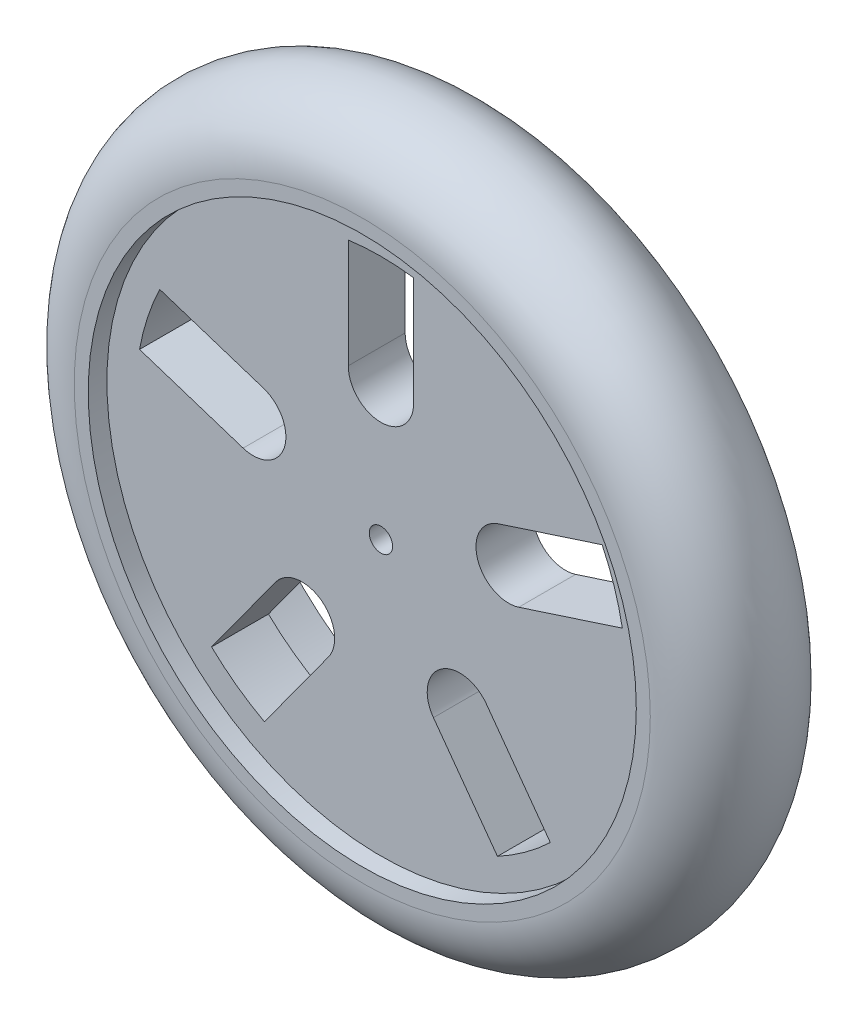
SolidWorks part; units mm, degrees
ref_plane "Front Plane" through (0, 0, 0) normal (0, 0, 1) x (1, 0, 0)
ref_plane "Top Plane" through (0, 0, 0) normal (0, 1, 0) x (1, 0, 0)
ref_plane "Right Plane" through (0, 0, 0) normal (1, 0, 0) x (0, 0, -1)
sketch "Sketch1" plane through (0, 0, 0) normal (1, 0, 0) x (0, 0, -1)
  line L0 (45.339, 0) -> (-45.339, 0)
  line L2 (-45.339, 195.961) -> (-45.339, 0)
  line L3 (-45.339, 0) -> (45.339, 0) construction
  line L4 (45.339, 195.961) -> (45.339, 0)
  arc A0 (45.339, 195.961) -> (-45.339, 195.961) centre (0, 195.961) ccw
  dimension "D1" = 90.678
  dimension "D2" = 195.961
revolve "Revolve1" add sketch "Sketch1" angle 360 about L3
sketch "Sketch2" plane through (0, 0, 45.339) normal (0, 0, 1) x (1, 0, 0)
  circle A0 centre (0, 0) radius 7.9375
  dimension "D1" = 15.875
extrude "Extrude1" cut sketch "Sketch2" against normal through all
sketch "Sketch3" plane through (0, 0, -45.339) normal (0, 0, -1) x (-1, 0, 0)
  circle A0 centre (0, 0) radius 186.436
  circle A1 centre (0, 0) radius 12.7
  dimension "D1" = 25.4
  dimension "D2" = 372.872
extrude "Extrude2" cut sketch "Sketch3" against normal blind 12.2936
sketch "Sketch4" plane through (0, 0, -33.0454) normal (0, 0, -1) x (-1, 0, 0)
  circle A0 centre (0, 0) radius 12.7
  circle A2 centre (0, 0) radius 186.436
  circle A3 centre (0, 0) radius 186.436
  dimension "D1" = 0
extrude "Extrude4" cut sketch "Sketch4" against normal blind 26.9875
sketch "Sketch5" plane through (0, 0, 45.339) normal (0, 0, 1) x (1, 0, 0)
  circle A0 centre (0, 0) radius 186.436
  dimension "D1" = 372.872
extrude "Extrude5" cut sketch "Sketch5" against normal blind 12.7
sketch "Sketch6" plane through (0, 0, 32.639) normal (0, 0, 1) x (1, 0, 0)
  line L0 (0, 194.4917) -> (0, 105.5917) construction
  line L1 (150.4893, 72.2657) -> (80.0157, 49.3674)
  line L2 (-22.225, 165.4551) -> (-22.225, 91.3548)
  line L3 (164.2251, 29.9912) -> (93.7515, 7.0929)
  line L4 (22.225, 165.4551) -> (22.225, 91.3548)
  line L5 (115.2325, -120.7925) -> (71.6774, -60.844)
  line L6 (79.2717, -146.9195) -> (35.7166, -86.9711)
  line L7 (-79.2717, -146.9195) -> (-35.7166, -86.9711)
  line L8 (-115.2325, -120.7925) -> (-71.6774, -60.844)
  line L9 (-164.2251, 29.9912) -> (-93.7515, 7.0929)
  line L10 (-150.4893, 72.2657) -> (-80.0157, 49.3674)
  arc A0 (22.225, 165.4551) -> (-22.225, 165.4551) centre (0, 0) ccw
  arc A1 (-22.225, 91.3548) -> (22.225, 91.3548) centre (0, 91.3548) ccw
  arc A2 (164.2251, 29.9912) -> (150.4893, 72.2657) centre (0, 0) ccw
  arc A3 (80.0157, 49.3674) -> (93.7515, 7.0929) centre (86.8836, 28.2302) ccw
  arc A4 (79.2717, -146.9195) -> (115.2325, -120.7925) centre (0, 0) ccw
  arc A5 (71.6774, -60.844) -> (35.7166, -86.9711) centre (53.697, -73.9076) ccw
  arc A6 (-115.2325, -120.7925) -> (-79.2717, -146.9195) centre (0, 0) ccw
  arc A7 (-35.7166, -86.9711) -> (-71.6774, -60.844) centre (-53.697, -73.9076) ccw
  arc A8 (-150.4893, 72.2657) -> (-164.2251, 29.9912) centre (0, 0) ccw
  arc A9 (-93.7515, 7.0929) -> (-80.0157, 49.3674) centre (-86.8836, 28.2302) ccw
  dimension "D2" = 44.45
extrude "Extrude6" cut sketch "Sketch6" against normal through all
